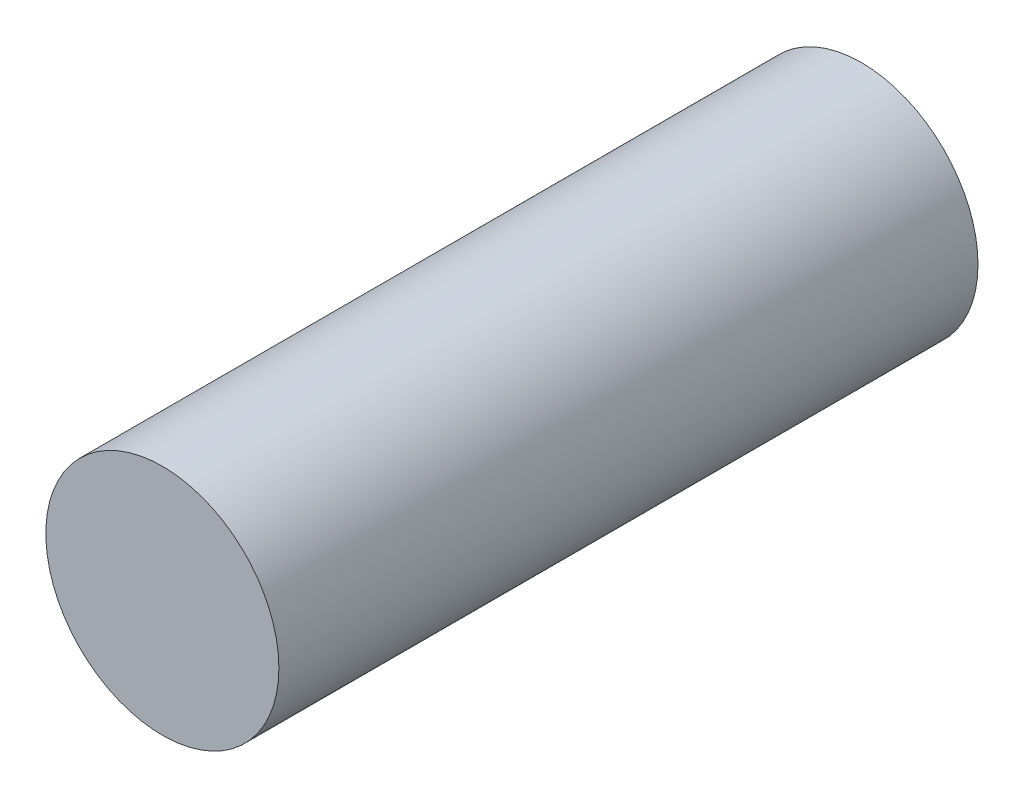
SolidWorks part; units mm, degrees
ref_plane "前视基准面" through (0, 0, 0) normal (0, 0, 1) x (1, 0, 0)
ref_plane "上视基准面" through (0, 0, 0) normal (0, 1, 0) x (1, 0, 0)
ref_plane "右视基准面" through (0, 0, 0) normal (1, 0, 0) x (0, 0, -1)
sketch "草图1" plane through (0, 0, 0) normal (0, 0, 1) x (1, 0, 0)
  circle A0 centre (-120.2381, 50.1851) radius 15
extrude "凸台-拉伸1" add sketch "草图1" against normal up to surface (90 mm away)
